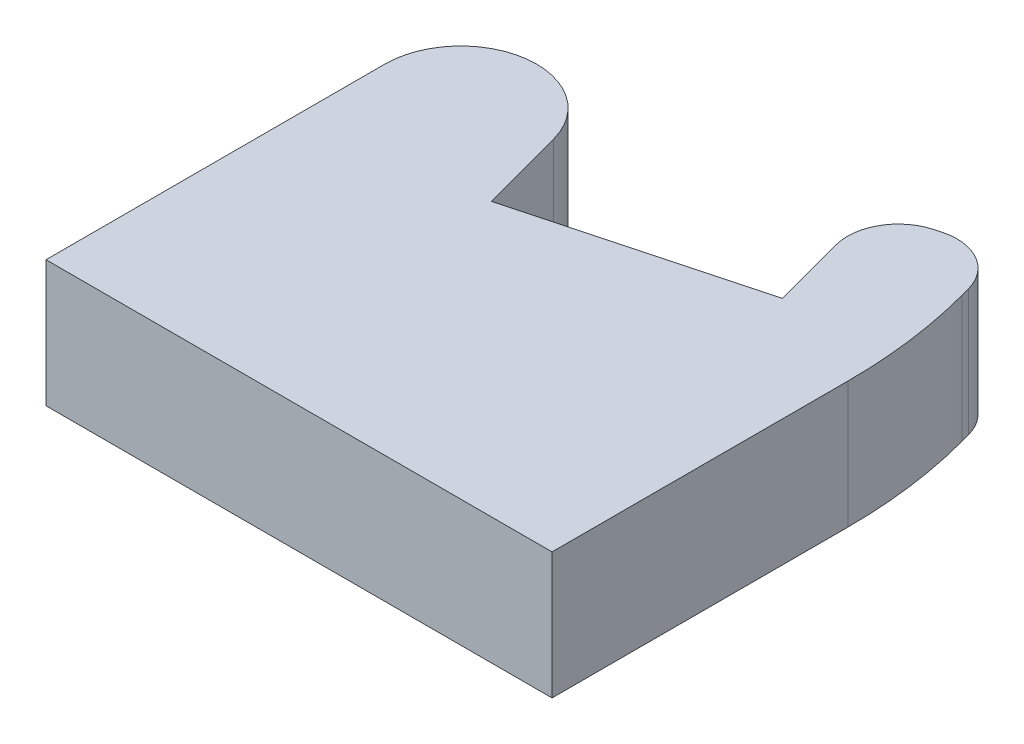
SolidWorks part; units mm, degrees
ref_plane "Front Plane" through (0, 0, 0) normal (0, 0, 1) x (1, 0, 0)
ref_plane "Top Plane" through (0, 0, 0) normal (0, 1, 0) x (1, 0, 0)
ref_plane "Right Plane" through (0, 0, 0) normal (1, 0, 0) x (0, 0, -1)
sketch "Sketch1" plane through (0, 0, 0) normal (0, 1, 0) x (1, 0, 0)
  line L0 (0, 0) -> (25.4, 0)
  line L1 (25.4, 0) -> (25.4, 14.8639)
  line L2 (20.1672, 16.8058) -> (8.636, 13.716)
  line L3 (8.636, 13.716) -> (7.4902, 17.9923)
  line L4 (0, 17.0062) -> (0, 0)
  line L5 (8.636, 13.716) -> (17.4524, 13.716) construction
  line L6 (20.1672, 16.8058) -> (19.1811, 20.486)
  line L7 (20.9772, 23.5968) -> (21.303, 23.6841)
  line L8 (24.4139, 21.8881) -> (24.5345, 21.4379)
  arc A0 (7.4902, 17.9923) -> (0, 17.0062) centre (3.81, 17.0062) ccw
  arc A1 (21.303, 23.6841) -> (24.4139, 21.8881) centre (21.9604, 21.2307) cw
  arc A2 (19.1811, 20.486) -> (20.9772, 23.5968) centre (21.6346, 21.1434) cw
  arc A3 (25.4, 14.8639) -> (24.5345, 21.4379) centre (0, 14.8639) ccw
  point P16 (18.5237, 22.9394)
  dimension "D4" = 3.81
  dimension "D8" = 2.54
  dimension "D9" = 25.4
  dimension "D1" = 25.4
  dimension "D2" = 8.636
  dimension "D3" = 13.716
  dimension "D5" = 15
  dimension "D6" = 11.938
  dimension "D7" = 6.35
extrude "Boss-Extrude1" add sketch "Sketch1" along normal blind 6.35
